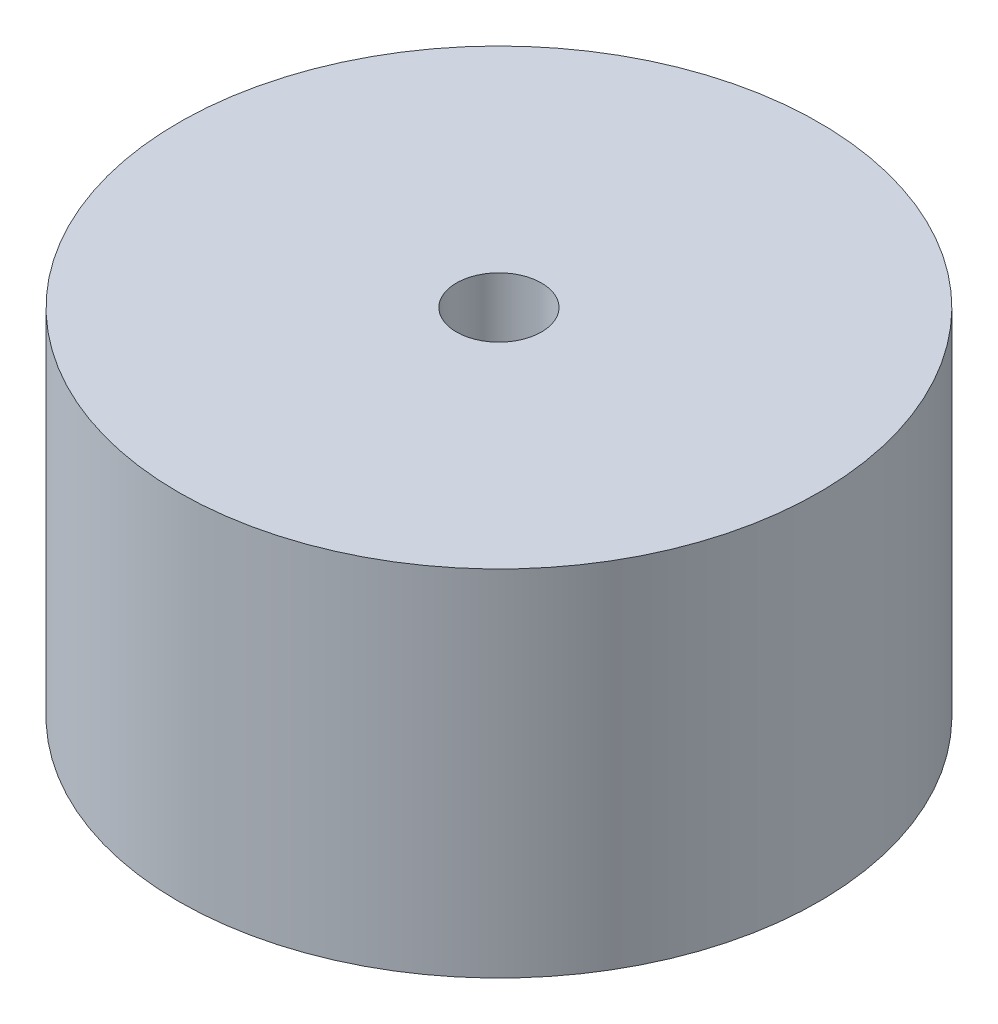
SolidWorks part; units mm, degrees
ref_plane "Front Plane" through (0, 0, 0) normal (0, 0, 1) x (1, 0, 0)
ref_plane "Top Plane" through (0, 0, 0) normal (0, 1, 0) x (1, 0, 0)
ref_plane "Right Plane" through (0, 0, 0) normal (1, 0, 0) x (0, 0, -1)
sketch "Sketch1" plane through (0, 0, 0) normal (0, 1, 0) x (1, 0, 0)
  circle A0 centre (0, 0) radius 14.351
  circle A1 centre (0, 0) radius 1.905
  dimension "D1" = 28.702
  dimension "D2" = 3.81
extrude "Boss-Extrude1" add sketch "Sketch1" along normal blind 15.875
sketch "Sketch2" plane through (0, 0, 0) normal (0, -1, 0) x (1, 0, 0)
  line L0 (0, -14.351) -> (0, 14.351) construction
  circle A0 centre (0, 0) radius 14.351 construction
  point P6 (0, 14.351)
  point P7 (0, 0)
